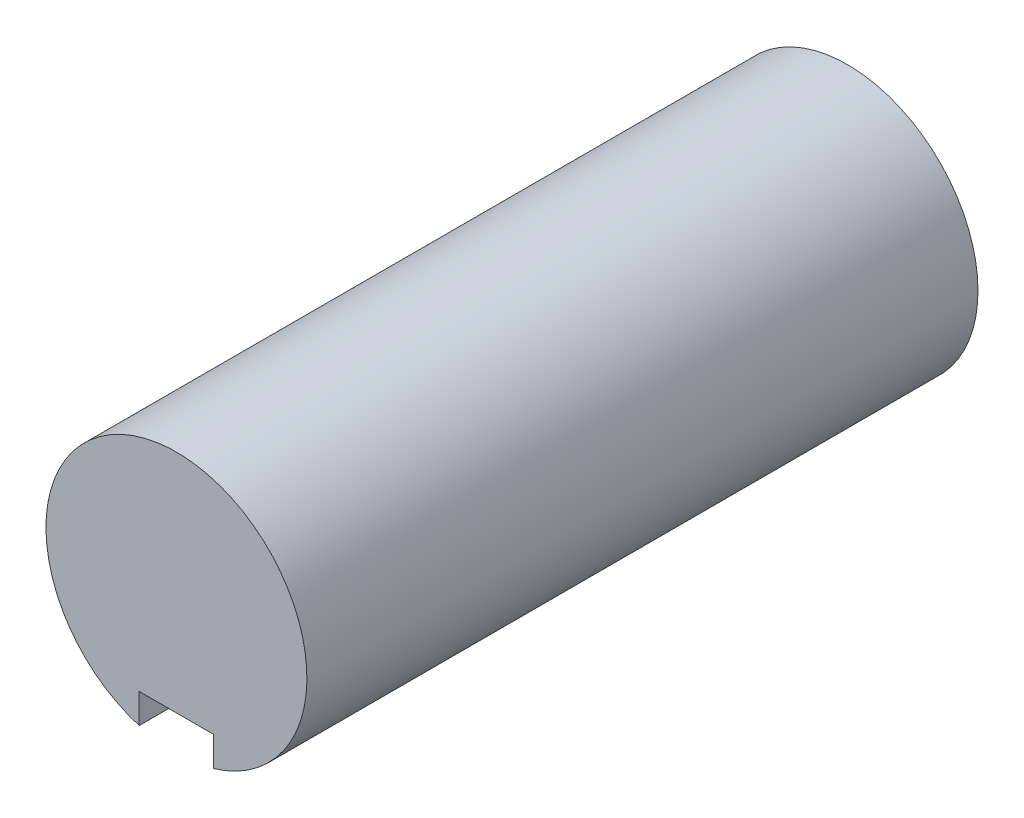
SolidWorks part; units mm, degrees
ref_plane "Front Plane" through (0, 0, 0) normal (0, 0, 1) x (1, 0, 0)
ref_plane "Top Plane" through (0, 0, 0) normal (0, 1, 0) x (1, 0, 0)
ref_plane "Right Plane" through (0, 0, 0) normal (1, 0, 0) x (0, 0, -1)
sketch "Sketch1" plane through (0, 0, 0) normal (0, 0, 1) x (1, 0, 0)
  line L2 (-5, -16.7705) -> (-5, -12.8)
  line L3 (-5, -12.8) -> (5, -12.8)
  line L4 (5, -16.7705) -> (5, -12.8)
  arc A0 (5, -16.7705) -> (-5, -16.7705) centre (0, 0) ccw
  point P3 (0, -17.5)
  dimension "D1" = 35
  dimension "D2" = 10
  dimension "D3" = 4.7
extrude "Boss-Extrude1" add sketch "Sketch1" along normal blind 90
sketch "Sketch2" plane through (0, 0, 0) normal (0, 0, -1) x (-1, 0, 0)
  line L0 (-5, -12.8) -> (-5, -16.7705) construction
  line L1 (5, -16.7705) -> (5, -12.8) construction
  line L2 (5, -12.8) -> (-5, -12.8) construction
  line L3 (-5, -12.8) -> (-5, -16.7705)
  line L4 (5, -16.7705) -> (5, -12.8)
  line L5 (5, -12.8) -> (-5, -12.8)
  arc A0 (-5, -16.7705) -> (5, -16.7705) centre (0, 0) ccw
  arc A1 (5, -16.7705) -> (-5, -16.7705) centre (0, 0) ccw construction
  line M1 (-5, -16.7705) -> (-5, -12.8)
  line M2 (-5, -12.8) -> (5, -12.8)
  line M3 (5, -12.8) -> (5, -16.7705)
extrude "Boss-Extrude2" add sketch "Sketch2" against normal blind 38 contours A0 M1 M3 M2
